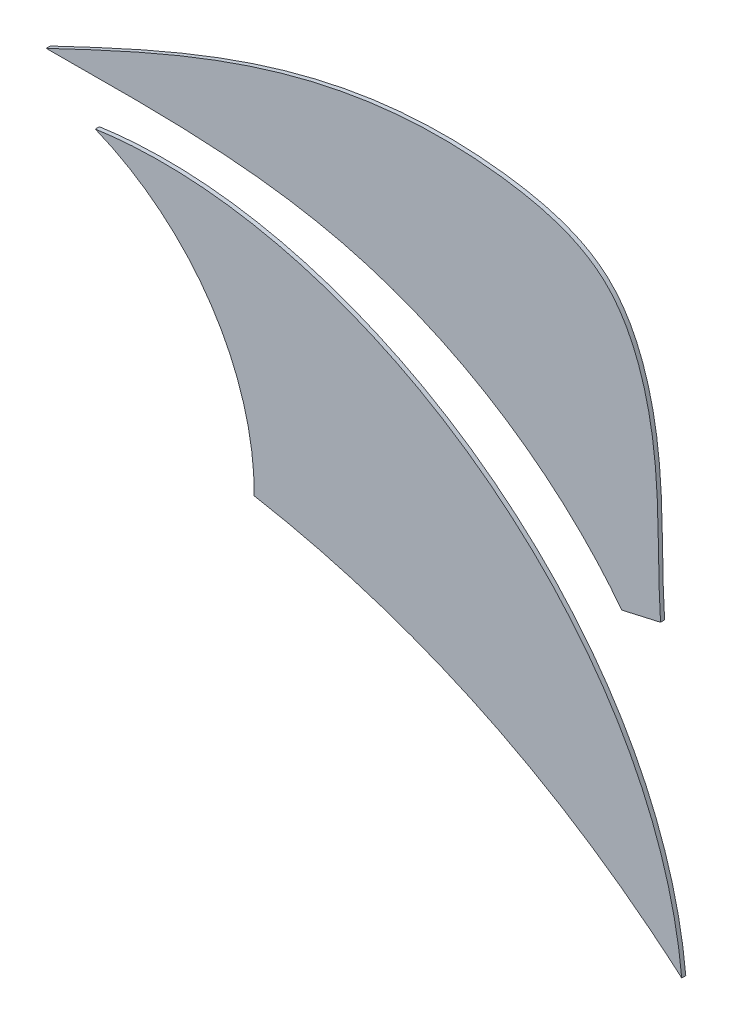
SolidWorks part; units mm, degrees
ref_plane "前视基准面" through (0, 0, 0) normal (0, 0, 1) x (1, 0, 0)
ref_plane "上视基准面" through (0, 0, 0) normal (0, 1, 0) x (1, 0, 0)
ref_plane "右视基准面" through (0, 0, 0) normal (1, 0, 0) x (0, 0, -1)
other "Configuration Table"
sketch "草图1" plane through (0, 0, 0) normal (0, 0, 1) x (1, 0, 0)
  line L0 (-21.4304, 56.0753) -> (-15.7324, 57.3725) construction
  line L1 (-21.4304, 56.0753) -> (-15.7324, 57.3725)
  arc A0 (-75.6159, 43.5701) -> (-99.0383, 78.6783) centre (-113.1802, 43.8763) ccw construction
  arc A1 (-75.6159, 43.5701) -> (-99.0383, 78.6783) centre (-113.1802, 43.8763) ccw
  parabola Q0 (-75.6159, 43.5701) -> (-12.6041, 13.5285) focus (-68.5837, -24.7624) apex (-40.566, 32.1653) construction
  parabola Q1 (-75.6159, 43.5701) -> (-12.6041, 13.5285) focus (-68.5837, -24.7624) apex (-40.566, 32.1653)
  spline S0 degree 3 poles (2965.8601, -224.668) (-250.4738, -84.4766) (16.8731, 3.769) (-23.0529, 99.1548) (-208.6692, 145.9227) (-271.8539, -525.0278) (-593.8728, 3033.3775) knots -1.806215 -1.806215 -1.806215 -1.806215 0.217981 0.320733 0.449687 4.345746 4.345746 4.345746 4.345746 only from (-15.7324, 57.3725) to (-106.2802, 85.3605) construction
  spline S1 degree 3 poles (643.7073, 2980.0475) (-422.9565, -232.7558) (40.6473, 493.6317) (133.3806, -438.0791) (-2958.7336, -304.8148) knots -4.082045 -4.082045 -4.082045 -4.082045 0.491735 5.35162 5.35162 5.35162 5.35162 only from (-106.2802, 85.3605) to (-21.4304, 56.0753) construction
  spline S2 degree 3 poles (-2970.9988, 137.7896) (2970.7709, -1115.6754) (-2617.6073, 2054.9267) (1506.3618, -2403.9872) knots -3.394524 -3.394524 -3.394524 -3.394524 4.556207 4.556207 4.556207 4.556207 only from (-12.6041, 13.5285) to (-99.0383, 78.6783) construction
  spline S3 degree 3 poles (-15.7324, 57.3725) (-16.3529, 66.6177) (-15.0941, 80.1408) (-23.0529, 99.1548) (-58.2185, 108.0152) (-85.4083, 95.3036) (-106.2802, 85.3605) knots 0 0 0 0 0.217981 0.320733 0.449687 1 1 1 1
  spline S4 degree 3 poles (-106.2802, 85.3605) (-91.1852, 85.4156) (-59.0531, 86.3602) (-31.0882, 68.6732) (-21.4304, 56.0753) knots 0 0 0 0 0.491735 1 1 1 1
  spline S5 degree 3 poles (-12.6041, 13.5285) (-16.5763, 54.6632) (-59.4762, 84.3739) (-99.0383, 78.6783) knots 0 0 0 0 1 1 1 1
extrude "凸台-拉伸1" add sketch "草图1" along normal blind 0.6
